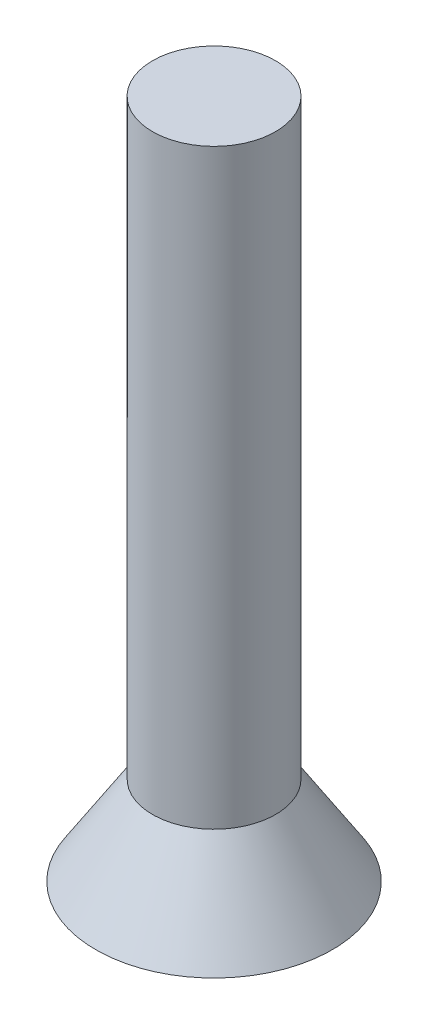
SolidWorks part; units mm, degrees
ref_plane "Front Plane" through (0, 0, 0) normal (0, 0, 1) x (1, 0, 0)
ref_plane "Top Plane" through (0, 0, 0) normal (0, 1, 0) x (1, 0, 0)
ref_plane "Right Plane" through (0, 0, 0) normal (1, 0, 0) x (0, 0, -1)
sketch "Sketch1" plane through (0, 0, 0) normal (0, 0, 1) x (1, 0, 0)
  line L0 (-3.175, 0) -> (3.175, 0)
  line L1 (-3.175, 0) -> (-1.651, 2.3813)
  line L2 (-1.651, 2.3813) -> (1.651, 2.3813) construction
  line L3 (1.651, 2.3813) -> (3.175, 0)
  line L4 (-1.651, 2.3813) -> (-1.651, 18.2563)
  line L5 (-1.651, 18.2563) -> (1.651, 18.2563)
  line L6 (1.651, 18.2563) -> (1.651, 2.3813)
  line L7 (0, 0) -> (0, -14.5981) construction
  line L8 (0, 0) -> (0, 18.2563)
  point P3 (0, 0)
  point P9 (0, 2.3813)
  dimension "D1" = 3.302
  dimension "D2" = 6.35
  dimension "D3" = 2.3813
  dimension "D4" = 15.875
revolve "Revolve3" add sketch "Sketch1" angle 360 about L7
